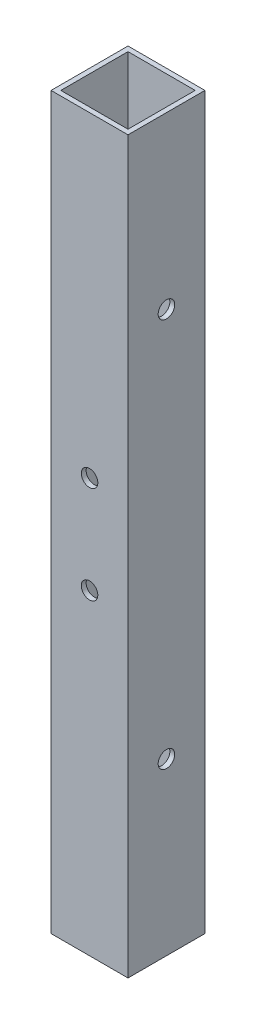
SolidWorks part; units mm, degrees
ref_plane "Front Plane" through (0, 0, 0) normal (0, 0, 1) x (1, 0, 0)
ref_plane "Top Plane" through (0, 0, 0) normal (0, 1, 0) x (1, 0, 0)
ref_plane "Right Plane" through (0, 0, 0) normal (1, 0, 0) x (0, 0, -1)
sketch "Sketch1" plane through (0, 0, 0) normal (0, 1, 0) x (1, 0, 0)
  line L0 (-6.9, -6.9) -> (-6.9, 6.9)
  line L1 (-7.9, -7.9) -> (7.9, -7.9)
  line L2 (-7.9, -7.9) -> (-7.9, 7.9)
  line L3 (-7.9, 7.9) -> (7.9, 7.9)
  line L4 (7.9, -7.9) -> (7.9, 7.9)
  line L5 (-7.9, -7.9) -> (7.9, 7.9) construction
  line L6 (-7.9, 7.9) -> (7.9, -7.9) construction
  line L7 (-6.9, 6.9) -> (6.9, 6.9)
  line L8 (6.9, -6.9) -> (6.9, 6.9)
  line L9 (-6.9, -6.9) -> (6.9, -6.9)
  point P0 (0, 0)
  dimension "D1" = 1
extrude "Boss-Extrude1" add sketch "Sketch1" along normal blind 150
sketch "Sketch2" plane through (-7.9, 0, 0) normal (-1, 0, 0) x (0, 0, 1)
  circle A0 centre (0, 115) radius 1.7
  circle A2 centre (0, 35) radius 1.7
  dimension "D1" = 3.4
  dimension "D2" = 80
extrude "Cut-Extrude1" cut sketch "Sketch2" against normal through all
sketch "Sketch3" plane through (0, 0, 7.9) normal (0, 0, 1) x (1, 0, 0)
  circle A0 centre (0, 85) radius 1.7
  circle A1 centre (0, 65) radius 1.7
  point P2 (0, 0)
  point P5 (7.9, 75)
  point P6 (0, 84.7539)
  dimension "D2" = 3.4
  dimension "D1" = 20
extrude "Cut-Extrude3" cut sketch "Sketch3" against normal through all
